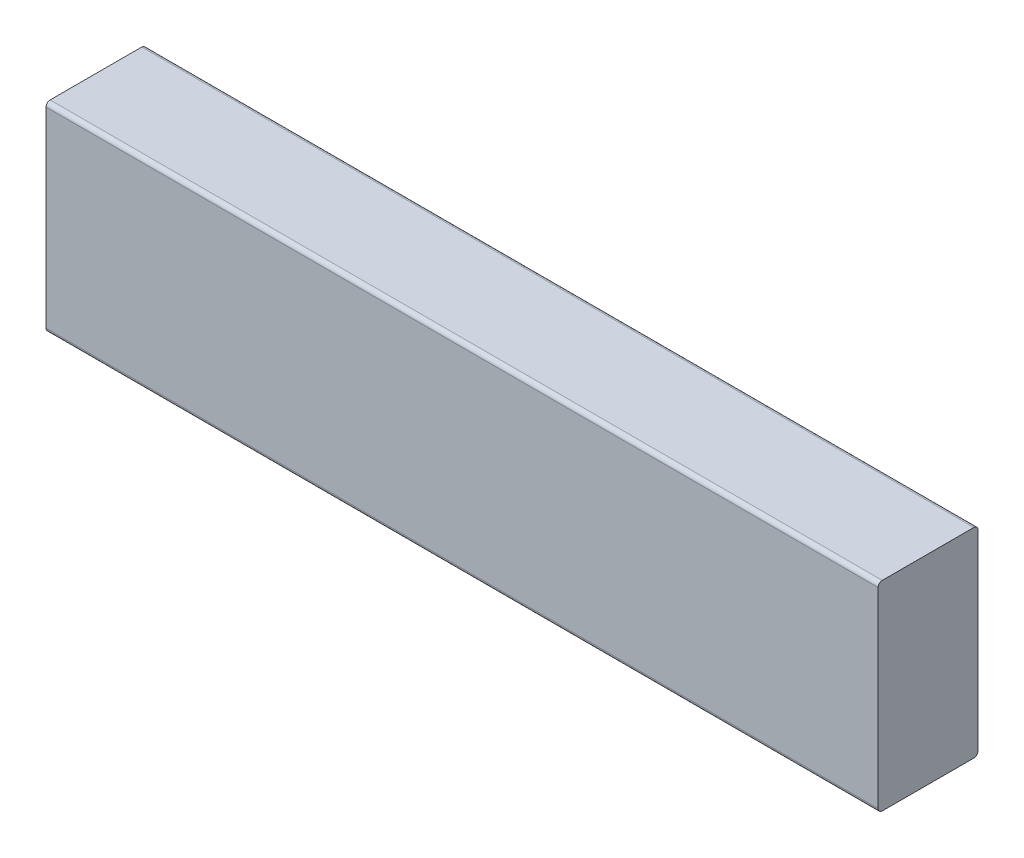
SolidWorks part; units mm, degrees
ref_plane "Front" through (0, 0, 0) normal (0, 0, 1) x (1, 0, 0)
ref_plane "Top" through (0, 0, 0) normal (0, 1, 0) x (1, 0, 0)
ref_plane "Right" through (0, 0, 0) normal (1, 0, 0) x (0, 0, -1)
sketch "Sketch1" plane through (0, 0, 0) normal (0, 0, 1) x (1, 0, 0)
  line L0 (0, 6) -> (-44, 6)
  line L1 (-44, -6) -> (0, -6)
  line L2 (-44, 6) -> (-44, -6)
  arc A2 (0, 6) -> (0, -6) centre (0, 0) cw
  dimension "b" = 12
  dimension "l" = 50
extrude "Extrude1" add sketch "Sketch1" along normal blind 6
sketch "Sketch2" plane through (0, 0, 0) normal (0, 0, 1) x (1, 0, 0)
  line L2 (6, 6) -> (6, -6)
  line L6 (0, 6) -> (-44, 6)
  line L7 (-44, 6) -> (-44, -6)
  line L8 (-44, -6) -> (0, -6)
  line L9 (6, 6) -> (-44, 6)
  line L10 (-44, 6) -> (-44, -6)
  line L11 (-44, -6) -> (6, -6)
  arc A3 (0, -6) -> (0, 6) centre (0, 0) ccw
  arc A4 (0, -6) -> (0, 6) centre (0, 0) ccw construction
  dimension "D1" = 0
extrude "Extrude2" add sketch "Sketch2" along normal blind 6
fillet "Fillet1" radius 0.25 4 edges at (-19, -6, 0) (-19, -6, 6) (-19, 6, 0) (-19, 6, 6)
equation "\"D1@Extrude2\" = \"h@Extrude1\""
